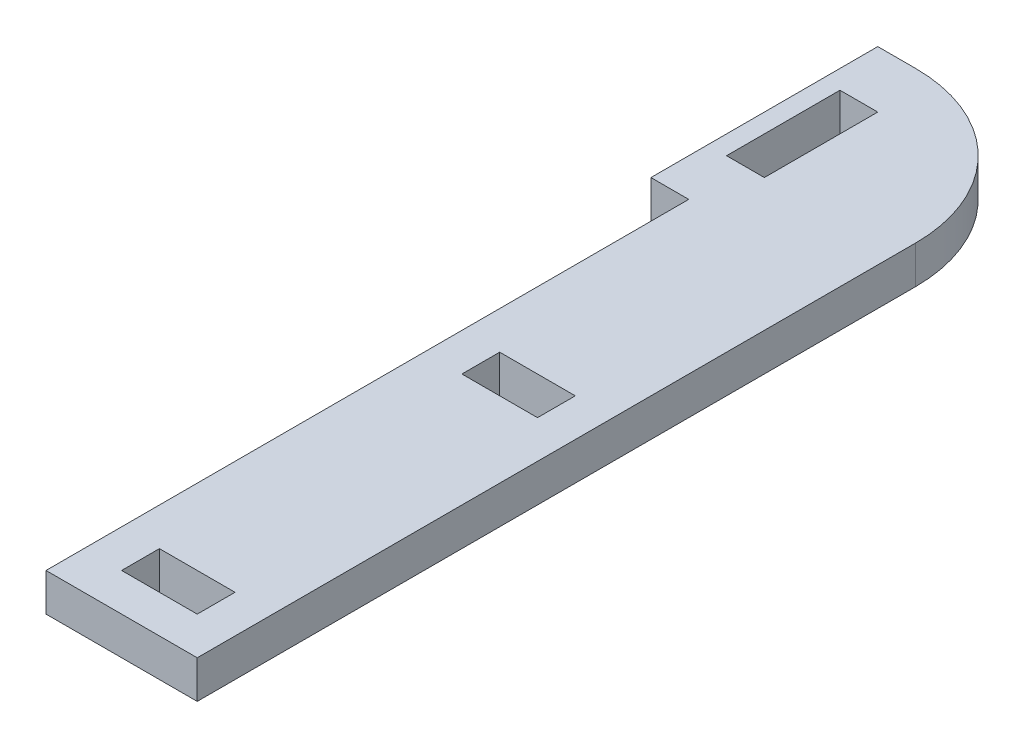
SolidWorks part; units mm, degrees
ref_plane "Front Plane" through (0, 0, 0) normal (0, 0, 1) x (1, 0, 0)
ref_plane "Top Plane" through (0, 0, 0) normal (0, 1, 0) x (1, 0, 0)
ref_plane "Right Plane" through (0, 0, 0) normal (1, 0, 0) x (0, 0, -1)
sketch "Sketch1" plane through (0, 0, 0) normal (0, 1, 0) x (1, 0, 0)
  line L1 (-25.0645, 20.0272) -> (-5.0645, 20.0272)
  line L2 (-25.0645, 20.0272) -> (-25.0645, 80.0272)
  line L4 (-5.0645, 20.0272) -> (-5.0645, 80.0272)
  line L5 (-20.0645, 25.0272) -> (-10.0645, 25.0272)
  line L6 (-20.0645, 25.0272) -> (-20.0645, 30.0272)
  line L7 (-20.0645, 30.0272) -> (-10.0645, 30.0272)
  line L8 (-10.0645, 25.0272) -> (-10.0645, 30.0272)
  line L9 (-20.0645, 70.0272) -> (-10.0645, 70.0272)
  line L10 (-20.0645, 70.0272) -> (-20.0645, 75.0272)
  line L11 (-20.0645, 75.0272) -> (-10.0645, 75.0272)
  line L12 (-10.0645, 70.0272) -> (-10.0645, 75.0272)
  line L14 (-30.0645, 105.0272) -> (-25.0645, 105.0272)
  line L15 (-30.0645, 105.0272) -> (-30.0645, 135.0272)
  line L16 (-30.0645, 135.0272) -> (-25.0645, 135.0272)
  line L21 (-5.0645, 80.0272) -> (-5.0645, 115.0272)
  line L23 (-25.0645, 80.0272) -> (-25.0645, 105.0272)
  line L24 (-27.5645, 112.5272) -> (-22.5645, 112.5272)
  line L25 (-27.5645, 112.5272) -> (-27.5645, 127.5272)
  line L26 (-27.5645, 127.5272) -> (-22.5645, 127.5272)
  line L27 (-22.5645, 112.5272) -> (-22.5645, 127.5272)
  line L31 (-22.5645, 120.0272) -> (30.1011, 120.0272) construction
  arc A0 (-5.0645, 115.0272) -> (-25.0645, 135.0272) centre (-25.0645, 115.0272) ccw
  point P12 (-25.0645, 120.0272)
  point P14 (-27.5645, 120.0272)
  point P21 (-25.0645, 115.0272)
  dimension "D1" = 20
  dimension "D2" = 5
  dimension "D3" = 5
  dimension "D4" = 10
  dimension "D5" = 5
  dimension "D6" = 40
  dimension "D7" = 5
  dimension "D8" = 5
  dimension "D9" = 5
  dimension "D10" = 30
  dimension "D11" = 20
  dimension "D12" = 5
  dimension "D13" = 5
  dimension "D14" = 15
  dimension "D15" = 2.5
extrude "Boss-Extrude1" add sketch "Sketch1" along normal blind 5
